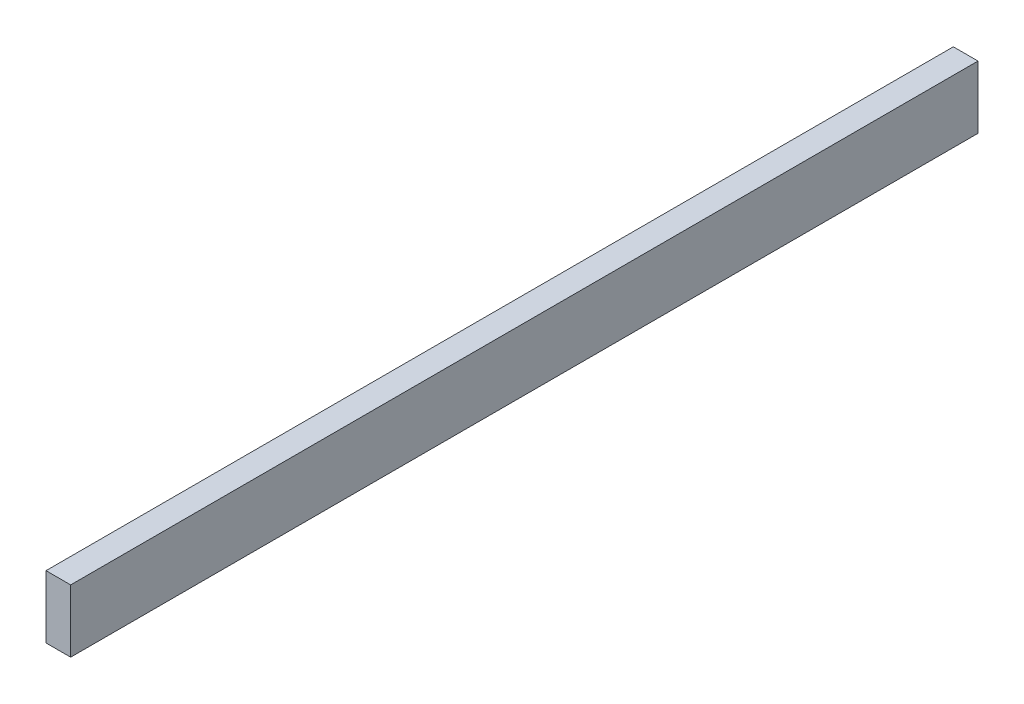
SolidWorks part; units mm, degrees
ref_plane "Front" through (0, 0, 0) normal (0, 0, 1) x (1, 0, 0)
ref_plane "Top" through (0, 0, 0) normal (0, 1, 0) x (1, 0, 0)
ref_plane "Right" through (0, 0, 0) normal (1, 0, 0) x (0, 0, -1)
sketch "Sketch1" plane through (0, 0, 0) normal (1, 0, 0) x (0, 0, -1)
  line L1 (-92, 6.35) -> (92, 6.35)
  line L2 (-92, 6.35) -> (-92, -6.35)
  line L3 (-92, -6.35) -> (92, -6.35)
  line L4 (92, 6.35) -> (92, -6.35)
  line L5 (-92, 6.35) -> (92, -6.35) construction
  line L6 (-92, -6.35) -> (92, 6.35) construction
  point P0 (0, 0)
  dimension "D1" = 184
  dimension "D2" = 12.7
extrude "Boss-Extrude1" add sketch "Sketch1" along normal blind 5
